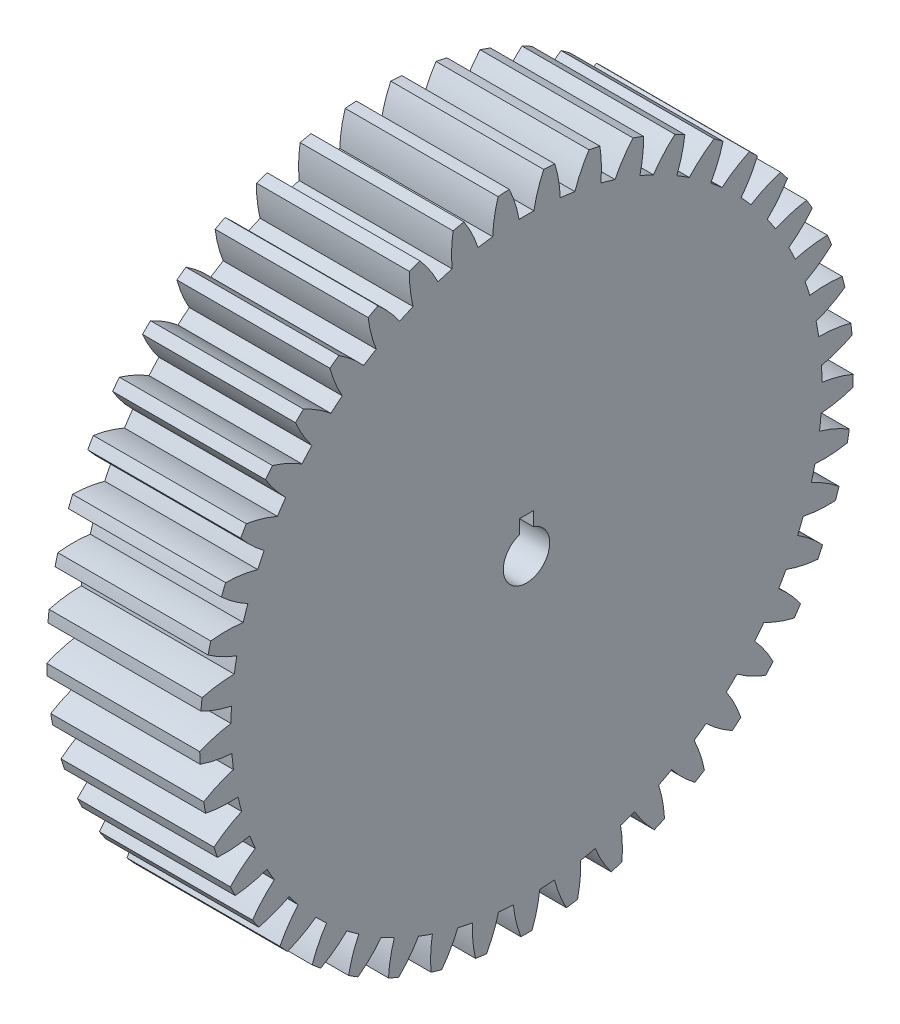
SolidWorks part; units mm, degrees
ref_plane "Plane1" through (0, 0, 0) normal (0, 0, 1) x (1, 0, 0)
ref_plane "Plane2" through (0, 0, 0) normal (0, 1, 0) x (1, 0, 0)
ref_plane "Plane3" through (0, 0, 0) normal (1, 0, 0) x (0, 0, -1)
sketch "HoldingSke" plane through (0, 0, 0) normal (0, 1, 0) x (1, 0, 0)
  line L0 (0, 0) -> (0.4714, -0.4714)
  line L1 (-15, 0) -> (100, 0) construction
  line L2 (0, 0) -> (-2.1039, 2.3779)
  line L3 (0, 0) -> (-11.863, 4.5341)
  line L4 (0, 0) -> (6.1066, 6.1066)
  line L5 (0, 0) -> (-46.8476, -17.4728)
  line L6 (0, 0) -> (-9.9476, -6.7116)
  line L7 (-2.1039, 2.3779) -> (8.6586, 51.2059)
  line L8 (-76.2, 54.61) -> (-76.1, 54.61)
  line L9 (-67.7845, 28.3722) -> (-49.3413, 33.142)
  line L10 (-76.2, 71.12) -> (104.1128, 71.12)
  line L11 (0, 0) -> (-12, 0)
  line L12 (-76.2, 101.6) -> (-76.147, 101.6)
  line L13 (24.9733, 27.94) -> (52.9518, 28.4284)
  line L14 (24.9733, 27.94) -> (24.9743, 27.94)
  line L15 (24.9733, 27.94) -> (100.4006, 29.5858)
  line L16 (-63.627, -1.5) -> (-12.827, -1.5)
  circle A0 centre (0, 0) radius 0.4
  circle A1 centre (0, 0) radius 31.874
  circle A2 centre (0, 0) radius 37.5
  circle A3 centre (0, 0) radius 0.4
  dimension "MHD" = 63.748
  dimension "Hub_dia" = 75
  dimension "Bore" = 0.8
  dimension "MBD" = 0.8
  dimension "Num_teeth" = 45
  dimension "Pitch" = 0.6667
  dimension "Overall_len" = 50
  dimension "Show_teeth" = 45
  dimension "Thickness" = 12
  dimension "OAL" = 50.0001
  dimension "T_dim" = 0.1
  dimension "Ap" = 14.5
  dimension "H" = 19.05
  dimension "Pitch_radius" = 180.3128
  dimension "Width" = 12
  dimension "Backlash" = 0.053
  dimension "Addendum_fac" = 1
  dimension "Dedendum_fac" = 1.25
  dimension "Clearance_fac" = 0.25
  dimension "Dedendum_add" = 0.001
  dimension "Module" = 1.5
sketch "BasProSke" plane through (0, 0, 0) normal (0, 1, 0) x (1, 0, 0)
  line L0 (-10, 0) -> (60, 0) construction
  line L1 (0, 0) -> (0, 35.25)
  line L2 (0, 0) -> (16.5, 0)
  line L3 (16.5, 0) -> (16.5, 35.25)
  line L4 (16.5, 35.25) -> (0, 35.25)
  dimension "Thickness" = 16.5
  dimension "Diameter" = 70.5
revolve "Base-Revolve" add sketch "BasProSke" angle 360 about L0
sketch "TooCutSke" plane through (0, 0, 0) normal (1, 0, 0) x (0, 0, -1)
  line L1 (0, 0) -> (0, 107) construction
  line L2 (0, 0) -> (-1.2706, 33.7261) construction
  line L3 (0, 0) -> (-4.7061, 67.3008) construction
  line L4 (-1.2706, 33.7261) -> (-2.3531, 33.6504) construction
  arc A0 (0.798, 31.864) -> (-0.798, 31.864) centre (0, 0) ccw
  arc A1 (1.8689, 35.2259) -> (-1.8689, 35.2259) centre (0, 0) ccw
  circle A2 centre (0, 0) radius 33.75 construction
  circle A3 centre (0, 0) radius 32.675 construction
  arc A4 (-0.798, 31.864) -> (-1.8689, 35.2259) centre (-14.0864, 29.4827) ccw
  arc A5 (1.8689, 35.2259) -> (0.798, 31.864) centre (14.0864, 29.4827) ccw
  dimension "Root_dia" = 63.748
  dimension "Overcut_dia" = 70.5508
  dimension "Pitch_dia" = 67.5
  dimension "Base_dia" = 65.35
  dimension "Flank_rad" = 13.5
  dimension "Half_ang" = 4
  dimension "Half_CT" = 1.0851
extrude "ToothCut" cut sketch "TooCutSke" along normal through all
fillet "Breaks" [suppressed] radius 0.03
fillet "RootFillets" [suppressed] radius 0.376
pattern_circular "TeethCuts" count 45 every 8 about axis through (-10, 0, 0) along (1, 0, 0) of "ToothCut", "RootFillets", "Breaks"
sketch "HubNeaOneSke" plane through (0, 0, 0) normal (-1, 0, 0) x (0, 0, 1)
  circle A0 centre (0, 0) radius 31.874
  dimension "Diameter" = 63.748
extrude "HubNearOne" [suppressed] add sketch "HubNeaOneSke" along normal blind 33.5001
sketch "HubNeaBotSke" plane through (0, 0, 0) normal (-1, 0, 0) x (0, 0, 1)
  circle A0 centre (0, 0) radius 31.874
  dimension "Diameter" = 63.748
extrude "HubNearBoth" [suppressed] add sketch "HubNeaBotSke" along normal blind 16.75
ref_plane "FarPln" through (16.5, 0, 0) normal (1, 0, 0) x (0, 0, -1)
sketch "HubFarSke" plane through (16.5, 0, 0) normal (1, 0, 0) x (0, 0, -1)
  circle A0 centre (0, 0) radius 31.874
  dimension "Diameter" = 63.748
extrude "HubFar" [suppressed] add sketch "HubFarSke" along normal blind 16.75
sketch "BorSke" plane through (0, 0, 0) normal (1, 0, 0) x (0, 0, -1)
  circle A0 centre (0, 0) radius 0.4
  dimension "Diameter" = 0.8
extrude "Bore" cut sketch "BorSke" along normal mid plane 100.0001
sketch "KeySke" plane through (0, 0, 0) normal (1, 0, 0) x (0, 0, -1)
  line L0 (-0.05, 0) -> (-0.05, 0.5)
  line L1 (-0.05, 0.5) -> (0.05, 0.5)
  line L2 (0.05, 0.5) -> (0.05, 0)
  line L3 (0, 0) -> (0, 34) construction
  line L4 (-0.05, 0) -> (0.05, 0)
  dimension "Offset" = 0.5
  dimension "Width" = 0.1
extrude "Keyway" [suppressed] cut sketch "KeySke" along normal mid plane 100.0001
pattern_circular "Keyway2" [suppressed] count 2 every 90 about axis through (-10, 0, 0) along (1, 0, 0)
sketch "Croquis1" plane through (16.5, 0, 0) normal (1, 0, 0) x (0, 0, -1)
  line L0 (0, 1.8819) -> (0, 2.5) construction
  line L1 (0, 2.5) -> (0, 3.8662) construction
  line L2 (0, 3.8848) -> (0, 0) construction
  line L3 (-0.75, 3.8848) -> (0.75, 3.8848)
  line L4 (-0.75, 3.8848) -> (-0.75, 2.3848)
  line L6 (0.75, 3.8848) -> (0.75, 2.3848)
  arc A0 (-0.75, 2.3848) -> (0.75, 2.3848) centre (0, 0) ccw
  dimension "D1" = 5
  dimension "D2" = 1.5
  dimension "D3" = 1.5
sketch "Croquis2" plane through (0, 0, 0) normal (-1, 0, 0) x (0, 0, 1)
  circle A1 centre (0, 0) radius 10
  dimension "D1" = 20
extrude "Saliente-Extruir1" add sketch "Croquis2" along normal blind 10
extrude "Cortar-Extruir1" cut sketch "Croquis1" against normal through all
equation "' \"Module@HoldingSke\" = 6.35"
equation "' \"Num_teeth@HoldingSke\" = 12"
equation "' \"Ap@HoldingSke\" =  20"
equation "' \"Ap@HoldingSke\" = 20"
equation "' \"Width@HoldingSke\" = 0.5 * 25.4"
equation "' \"Hub_dia@HoldingSke\"= 1 * 25.4"
equation "' \"Hub_dia@HoldingSke\" = 1 * 25.4"
equation "' \"Overall_len@HoldingSke\" = 1.0 * 25.4"
equation "' \"Bore@HoldingSke\" = 0.75 * 25.4"
equation "' \"T_dim@HoldingSke\" = 0.1 * 25.4"
equation "' \"Width@KeySke\" = 0.25 * 25.4"
equation "' \"Show_teeth@HoldingSke\" = 13"
equation "' \"Backlash@HoldingSke\" = 0.009 * 25.4"
equation "' \"Addendum_fac@HoldingSke\" = 1.0"
equation "' \"Dedendum_fac@HoldingSke\" = 1.25"
equation "' \"Dedendum_add@HoldingSke\" = 0.00005 * 25.4"
equation "' \"Clearance_fac@HoldingSke\" = 0.25"
equation "\"Pitch@HoldingSke\" = 1 / \"Module@HoldingSke\""
equation "\"Overcut_dia@TooCutSke\" = (\"Num_teeth@HoldingSke\" + 2 * \"Addendum_fac@HoldingSke\") / \"Pitch@HoldingSke\" + 0.002 * 25.4"
equation "\"Pitch_dia@TooCutSke\" = \"Num_teeth@HoldingSke\" / \"Pitch@HoldingSke\""
equation "\"Base_dia@TooCutSke\" = \"Num_teeth@HoldingSke\" / \"Pitch@HoldingSke\" * cos((\"Ap@HoldingSke\"  * 3.14159265 / 180))"
equation "\"Root_dia@TooCutSke\" = (\"Num_teeth@HoldingSke\" + 2) / \"Pitch@HoldingSke\" - 2 * (\"Addendum_fac@HoldingSke\" + \"Dedendum_fac@HoldingSke\") / \"Pitch@HoldingSke\" - \"Dedendum_add@HoldingSke\" * 2"
equation "\"Half_ang@TooCutSke\" = 180 / \"Num_teeth@HoldingSke\""
equation "\"Half_CT@TooCutSke\" = \"Num_teeth@HoldingSke\" / \"Pitch@HoldingSke\" * sin((3.14159265 / 2 / \"Num_teeth@HoldingSke\")) / 2 - 7 * \"Backlash@HoldingSke\" / 4"
equation "\"Flank_rad@TooCutSke\" = \"Num_teeth@HoldingSke\" / \"Pitch@HoldingSke\" / 5"
equation "\"Radius@RootFillets\" = \"Clearance_fac@HoldingSke\" / \"Pitch@HoldingSke\" + \"Dedendum_add@HoldingSke\""
equation "\"Break_rad@Breaks\" = 0.02 / \"Pitch@HoldingSke\""
equation "\"Thickness@HoldingSke\" = \"Width@HoldingSke\""
equation "\"OAL@HoldingSke\" = \"Thickness@HoldingSke\""
equation "\"MHD@HoldingSke\" = (\"Num_teeth@HoldingSke\" + 2) / \"Pitch@HoldingSke\" - 2 * (\"Addendum_fac@HoldingSke\" + \"Dedendum_fac@HoldingSke\")  / \"Pitch@HoldingSke\" - \"Dedendum_add@HoldingSke\" * 2"
equation "\"MBD@HoldingSke\" = (\"Num_teeth@HoldingSke\" + 2) / \"Pitch@HoldingSke\" - 2 * (\"Addendum_fac@HoldingSke\" + \"Dedendum_fac@HoldingSke\")  / \"Pitch@HoldingSke\" - \"Dedendum_add@HoldingSke\" * 2 - 0.002 * 25.4"
equation "\"MHD@HoldingSke\" = ((sgn( \"MHD@HoldingSke\" - \"Hub_dia@HoldingSke\" )-1)*( \"MHD@HoldingSke\" - \"Hub_dia@HoldingSke\" ))/-2+ \"Hub_dia@HoldingSke\""
equation "\"MBD@HoldingSke\" = ((sgn( \"MBD@HoldingSke\" - \"Bore@HoldingSke\" )-1)*( \"MBD@HoldingSke\" - \"Bore@HoldingSke\" ))/-2+ \"Bore@HoldingSke\""
equation "\"OAL@HoldingSke\" = ((sgn( \"OAL@HoldingSke\" - \"Overall_len@HoldingSke\" )+1)*( \"OAL@HoldingSke\" - \"Overall_len@HoldingSke\" ))/2 + \"Overall_len@HoldingSke\" + 0.000002 * 25.4"
equation "\"Num_teeth@TeethCuts\" = int( \"Show_teeth@HoldingSke\" ) + 1"
equation "\"Num_teeth@TeethCuts\" = ((sgn( \"Num_teeth@TeethCuts\" - \"Num_teeth@HoldingSke\" )-1)*( \"Num_teeth@TeethCuts\" - \"Num_teeth@HoldingSke\" ))/-2+ \"Num_teeth@HoldingSke\""
equation "\"Num_teeth@TeethCuts\" = ((sgn( \"Num_teeth@TeethCuts\" - 2.0)+1)*( \"Num_teeth@TeethCuts\" - 2.0))/2 +2.0"
equation "\"Angle@TeethCuts\" = 360.0 / \"Num_teeth@HoldingSke\""
equation "\"Diameter@BasProSke\" = (\"Num_teeth@HoldingSke\" + 2 * \"Addendum_fac@HoldingSke\") / \"Pitch@HoldingSke\""
equation "' \"Fillet_rad@BasProSke\" =  \"Thickness@HoldingSke\" * 0.05"
equation "' \"Fillet_rad@BasProSke\" = \"Thickness@HoldingSke\" * 0.05"
equation "\"MHD@HoldingSke\" = ((sgn( \"MHD@HoldingSke\" - \"Root_dia@TooCutSke\" )-1)*( \"MHD@HoldingSke\" - \"Root_dia@TooCutSke\" ))/-2+ \"Root_dia@TooCutSke\""
equation "\"Diameter@HubNeaOneSke\" = \"MHD@HoldingSke\""
equation "\"Length@HubNearOne\" = \"OAL@HoldingSke\" - \"Thickness@BasProSke\""
equation "\"Diameter@HubNeaBotSke\" = \"MHD@HoldingSke\""
equation "\"Length@HubNearBoth\" = ( \"OAL@HoldingSke\" - \"Thickness@BasProSke\" ) / 2.0"
equation "\"Thickness@FarPln\" = \"Thickness@BasProSke\""
equation "\"Diameter@HubFarSke\" = \"MHD@HoldingSke\""
equation "\"Length@HubFar\" = ( \"OAL@HoldingSke\" - \"Thickness@BasProSke\" ) / 2.0"
equation "\"Diameter@BorSke\" = \"MBD@HoldingSke\""
equation "\"D1@Bore\" = \"OAL@HoldingSke\" * 2.0"
equation "\"D1@Keyway\" = \"OAL@HoldingSke\" * 2.0"
equation "\"Offset@KeySke\" = \"T_dim@HoldingSke\" + \"MBD@HoldingSke\" / 2.0"
